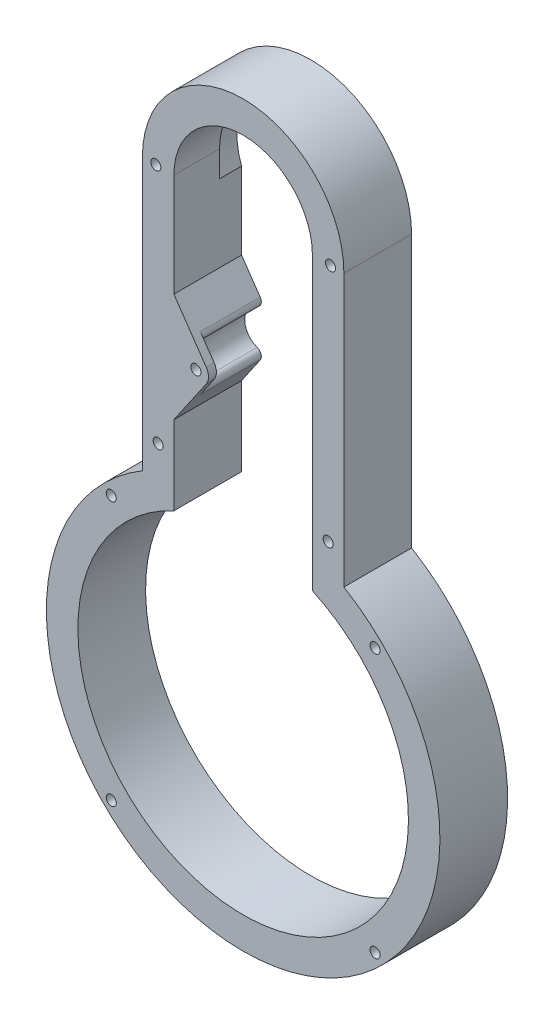
SolidWorks part; units mm, degrees
ref_plane "Front Plane" through (0, 0, 0) normal (0, 0, 1) x (1, 0, 0)
ref_plane "Top Plane" through (0, 0, 0) normal (0, 1, 0) x (1, 0, 0)
ref_plane "Right Plane" through (0, 0, 0) normal (1, 0, 0) x (0, 0, -1)
sketch "Sketch1" plane through (0, 0, 0) normal (0, 0, 1) x (1, 0, 0)
  line L0 (0, -40) -> (0, -180) construction
  line L6 (-32, -126.3134) -> (-32, -40)
  line L7 (32, -126.3134) -> (32, -40)
  line L8 (-22, -132.3319) -> (-22, -40)
  line L9 (22, -132.3319) -> (22, -40)
  arc A0 (32, -40) -> (-32, -40) centre (0, -40) ccw
  arc A3 (-32, -126.3134) -> (32, -126.3134) centre (0, -180) ccw
  arc A6 (-32, -126.3134) -> (32, -126.3134) centre (0, -180) ccw construction
  arc A7 (-32, -126.3134) -> (32, -126.3134) centre (0, -180) ccw construction
  circle A8 centre (0, -40) radius 20.0986 construction
  circle A9 centre (0, -40) radius 20.0986 construction
  arc A10 (22, -40) -> (-22, -40) centre (0, -40) ccw
  arc A11 (-22, -132.3319) -> (22, -132.3319) centre (0, -180) ccw
  arc A12 (32, -40) -> (-32, -40) centre (0, -40) ccw construction
  arc A13 (32, -40) -> (-32, -40) centre (0, -40) ccw construction
  point P21 (-32, -40)
  dimension "D1" = 10
extrude "Boss-Extrude1" add sketch "Sketch1" along normal up to surface (21.5 mm away)
sketch "Sketch3" plane through (0, 0, 21.5) normal (0, 0, 1) x (1, 0, 0)
  line L6 (32, -126.3134) -> (32, -40)
  line L7 (-32, -40) -> (-32, -126.3134)
  line L10 (32, -126.3134) -> (32, -40)
  line L11 (-32, -40) -> (-32, -126.3134)
  arc A2 (-32, -126.3134) -> (32, -126.3134) centre (0, -180) ccw
  arc A3 (-32, -126.3134) -> (32, -126.3134) centre (0, -180) ccw
  arc A7 (32, -40) -> (-32, -40) centre (0, -40) ccw
  arc A11 (32, -40) -> (-32, -40) centre (0, -40) ccw
  dimension "D1" = 0
sketch "Sketch4" plane through (0, 0, 21.5) normal (0, 0, 1) x (1, 0, 0)
  line L0 (-11.7023, -87.7361) -> (-22, -72.7361)
  line L1 (-22, -132.3319) -> (-22, -40) construction
  line L2 (-11.7023, -92.2639) -> (-22, -107.2639)
  circle A0 centre (-15, -90) radius 1.6
  arc A1 (-11.7023, -92.2639) -> (-11.7023, -87.7361) centre (-15, -90) ccw
  line M4 (-22, -132.3319) -> (-22, -40)
  dimension "D3" = 8
  dimension "D4" = 3.2
  dimension "D5" = 15
  dimension "D1" = 50
  dimension "D2" = 15
extrude "Boss-Extrude2" add sketch "Sketch4" against normal up to surface (21.5 mm away) contours L2 A1 L0 A0 M4 up to face at (0, -104.2034, 0)
sketch "Sketch5" plane through (0, 0, 0) normal (0, 0, -1) x (-1, 0, 0)
  circle A0 centre (15, -90) radius 6
  circle A1 centre (15, -90) radius 5 construction
  circle A2 centre (15, -90) radius 5 construction
  dimension "D1" = 1
extrude "Cut-Extrude1" cut sketch "Sketch5" against normal offset from surface (19 mm away) 0.5
fillet "Fillet1" radius 2 2 edges at (-14.2334, -95.9508, 9.5) (-14.2334, -84.0492, 9.5)
sketch "Sketch6" plane through (0, 0, 0) normal (0, 0, -1) x (-1, 0, 0)
  circle A0 centre (0, -40) radius 23.5 construction
  circle A1 centre (0, -40) radius 23.5 construction
  circle A2 centre (0, -40) radius 23.5
  dimension "D1" = 0
extrude "Cut-Extrude2" cut sketch "Sketch6" against normal up to surface (7 mm away)
sketch "Sketch7" plane through (0, 0, 0) normal (0, 0, -1) x (-1, 0, 0)
  circle A0 centre (41.8961, -221.8961) radius 1.6 construction
  circle A1 centre (-41.8961, -221.8961) radius 1.6 construction
  circle A2 centre (-41.8961, -138.1039) radius 1.6 construction
  circle A3 centre (41.8961, -138.1039) radius 1.6 construction
  circle A4 centre (41.8961, -221.8961) radius 1.6
  circle A5 centre (-41.8961, -221.8961) radius 1.6
  circle A6 centre (-41.8961, -138.1039) radius 1.6
  circle A7 centre (41.8961, -138.1039) radius 1.6
extrude "Cut-Extrude3" cut sketch "Sketch7" against normal through all
sketch "Sketch8" plane through (0, 0, 0) normal (0, 0, -1) x (-1, 0, 0)
  line L0 (23.5, -40) -> (32, -40) construction
  line L1 (0, 0) -> (0, -60.9762) construction
  line L2 (32, -116.3134) -> (22, -116.3134) construction
  line L3 (32, -40) -> (32, -126.3134) construction
  line L4 (22, -107.2639) -> (22, -132.3319) construction
  arc A0 (22, -48.2614) -> (-22, -48.2614) centre (0, -40) ccw construction
  arc A1 (22, -48.2614) -> (-22, -48.2614) centre (0, -40) ccw construction
  circle A2 centre (27.75, -40) radius 1.6
  circle A3 centre (27, -116.3134) radius 1.6
  circle A4 centre (-27.75, -40) radius 1.6
  circle A5 centre (-27, -116.3134) radius 1.6
  dimension "D1" = 3.2
  dimension "D2" = 10
extrude "Cut-Extrude4" cut sketch "Sketch8" against normal through all
